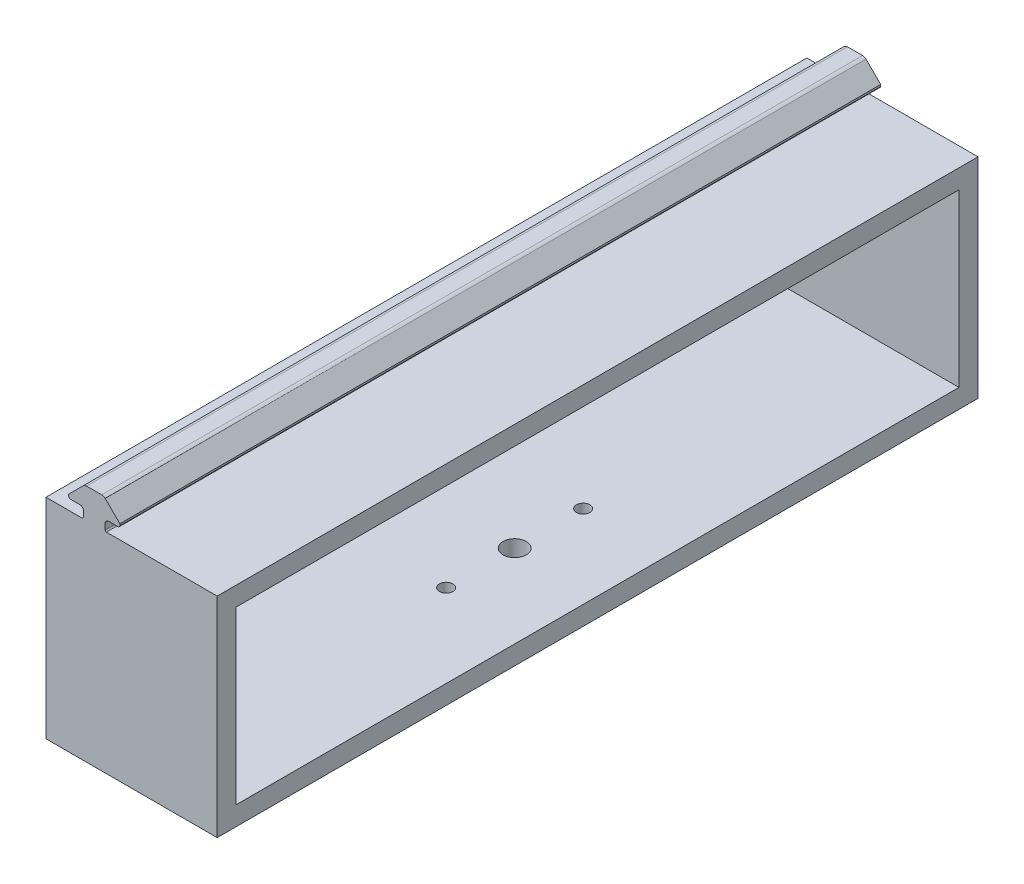
SolidWorks part; units mm, degrees
ref_plane "Front Plane" through (0, 0, 0) normal (0, 0, 1) x (1, 0, 0)
ref_plane "Top Plane" through (0, 0, 0) normal (0, 1, 0) x (1, 0, 0)
ref_plane "Right Plane" through (0, 0, 0) normal (1, 0, 0) x (0, 0, -1)
sketch "body sketch" plane through (0, 0, 0) normal (0, 0, 1) x (1, 0, 0)
  line L0 (-9.8141, 31.5907) -> (-9.8141, 23.3992) construction
  line L1 (-11.7928, 31.2966) -> (-7.8354, 31.2966)
  line L2 (-6.9378, 30.9425) -> (-3.0834, 27.088)
  line L3 (-3.0834, 27.088) -> (-3.0834, 26.6272)
  line L4 (-3.5442, 26.1664) -> (-6.0939, 26.1664)
  line L5 (-6.9378, 25.3225) -> (-6.9378, 23.7712)
  line L6 (-12.6904, 25.3225) -> (-12.6904, 23.7712)
  line L7 (-16.084, 26.1664) -> (-13.5343, 26.1664)
  line L8 (-16.5448, 27.088) -> (-16.5448, 26.6272)
  line L9 (-12.6904, 30.9425) -> (-16.5448, 27.088)
  line L10 (-12.9824, 23.4093) -> (-22.5, 23.4093)
  line L11 (-22.5, 23.4093) -> (-22.5, -31.5907)
  line L12 (-22.5, -31.5907) -> (22.5, -31.5907)
  line L13 (22.5, -31.5907) -> (22.5, 23.4093)
  line L14 (22.5, 23.4093) -> (-6.6458, 23.4093)
  arc A0 (-6.0939, 26.1664) -> (-6.9378, 25.3225) centre (-6.0704, 25.299) ccw
  arc A1 (-3.5442, 26.1664) -> (-3.0834, 26.6272) centre (-3.6789, 26.7619) ccw
  arc A2 (-6.9378, 23.7712) -> (-6.6458, 23.4093) centre (-6.5587, 23.7784) ccw
  arc A3 (-7.8354, 31.2966) -> (-6.9378, 30.9425) centre (-8.1959, 29.0683) cw
  arc A4 (-12.6904, 23.7712) -> (-12.9824, 23.4093) centre (-13.0695, 23.7784) cw
  arc A5 (-13.5343, 26.1664) -> (-12.6904, 25.3225) centre (-13.5578, 25.299) cw
  arc A6 (-16.084, 26.1664) -> (-16.5448, 26.6272) centre (-15.9493, 26.7619) cw
  arc A7 (-11.7928, 31.2966) -> (-12.6904, 30.9425) centre (-11.4323, 29.0683) ccw
  point P5 (-9.8141, 31.2966)
  point P32 (-9.8141, 31.2966)
extrude "Boss-Extrude1" add sketch "body sketch" along normal blind 200
sketch "body cut" plane through (22.5, 0, 0) normal (1, 0, 0) x (0, 0, -1)
  line L0 (-100, 23.4093) -> (-100, -31.5907) construction
  line L1 (-200, 23.4093) -> (0, 23.4093) construction
  line L2 (-200, -31.5907) -> (0, -31.5907) construction
  line L3 (-200, -4.0907) -> (0, -4.0907) construction
  line L4 (-200, -31.5907) -> (-200, 23.4093) construction
  line L5 (0, -31.5907) -> (0, 23.4093) construction
  line L7 (-195, -26.5907) -> (-5, -26.5907)
  line L8 (-195, -26.5907) -> (-195, 18.4093)
  line L9 (-195, 18.4093) -> (-5, 18.4093)
  line L10 (-5, -26.5907) -> (-5, 18.4093)
  line L11 (-195, -26.5907) -> (-5, 18.4093) construction
  line L12 (-195, 18.4093) -> (-5, -26.5907) construction
  point P12 (-100, -4.0907)
  dimension "D1" = 190
  dimension "D2" = 45
extrude "Cut-Extrude1" cut sketch "body cut" against normal through all both and the other way through all
sketch "screw holes" plane through (0, -31.5907, 0) normal (0, -1, 0) x (-1, 0, 0)
  line L0 (-23.3392, -100) -> (13.9588, -100) construction
  line L1 (22.5, -100) -> (-38.9995, -100) construction
  line L2 (22.5, -200) -> (22.5, 0) construction
  circle A0 centre (-0.7, -100) radius 3.0578
  circle A1 centre (-0.6963, -81.9999) radius 1.7645
  circle A2 centre (-0.6963, -117.9999) radius 1.7645
  point P2 (0, 0)
  dimension "D1" = 18.0001
  dimension "D2" = 17.9999
  dimension "D3" = 0
  dimension "D5" = 0
extrude "Cut-Extrude9" cut sketch "screw holes" against normal blind 10
